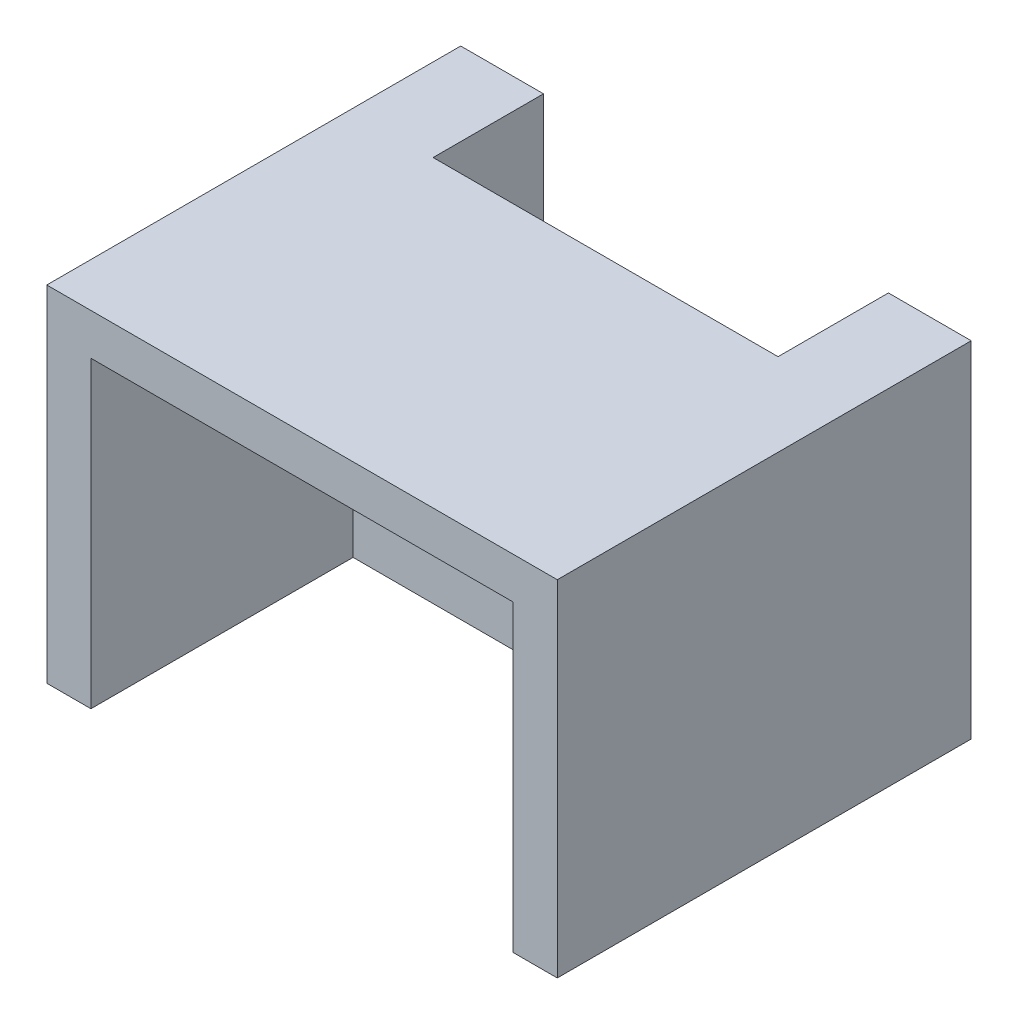
SolidWorks part; units mm, degrees
ref_plane "Front Plane" through (0, 0, 0) normal (0, 0, 1) x (1, 0, 0)
ref_plane "Top Plane" through (0, 0, 0) normal (0, 1, 0) x (1, 0, 0)
ref_plane "Right Plane" through (0, 0, 0) normal (1, 0, 0) x (0, 0, -1)
sketch "Sketch1" plane through (0, 0, 0) normal (1, 0, 0) x (0, 0, -1)
  line L0 (0, 0) -> (25, 0)
  line L1 (25, 0) -> (25, -25)
  line L2 (25, -25) -> (0, -25)
  line L3 (0, -25) -> (0, 0)
  dimension "D1" = 25
  dimension "D2" = 25
extrude "Boss-Extrude1" add sketch "Sketch1" along normal blind 37
sketch "Sketch2" plane through (0, -25, 0) normal (0, -1, 0) x (1, 0, 0)
  line L0 (3.2, 0) -> (3.2, -19)
  line L1 (37, 0) -> (0, 0) construction
  line L2 (3.2, -19) -> (33.8, -19)
  line L3 (33.8, -19) -> (33.8, 0)
  line L4 (33.8, 0) -> (3.2, 0)
  line L5 (18.5, -25) -> (18.5, -19) construction
  line L6 (37, -25) -> (0, -25) construction
  dimension "D1" = 30.6
  dimension "D2" = 6
extrude "Cut-Extrude1" cut sketch "Sketch2" against normal offset from surface (22 mm away) 3 up to face at (18.5, 0, -12.5)
sketch "Sketch3" plane through (0, 0, -25) normal (0, 0, -1) x (-1, 0, 0)
  line L0 (-37, 0) -> (0, 0) construction
  line L1 (-31, 0) -> (-6, 0)
  line L2 (-31, 0) -> (-31, -25)
  line L3 (-31, -25) -> (-6, -25)
  line L4 (-6, 0) -> (-6, -25)
  line L5 (-37, -25) -> (0, -25) construction
  line L6 (-18.5, 0) -> (-18.5, -25) construction
  dimension "D1" = 25
extrude "Cut-Extrude2" cut sketch "Sketch3" against normal blind 3
sketch "Sketch4" plane through (0, 0, -25) normal (0, 0, -1) x (-1, 0, 0)
  line L5 (-37, -25) -> (-31, -25)
  line L6 (-31, -25) -> (-31, 0)
  line L7 (-31, 0) -> (-37, 0)
  line L8 (-37, 0) -> (-37, -25)
  line L9 (-37, -25) -> (-31, -25)
  line L10 (-31, -25) -> (-31, 0)
  line L11 (-31, 0) -> (-37, 0)
  line L12 (-37, 0) -> (-37, -25)
  line L14 (0, 0) -> (-6, 0)
  line L15 (-6, 0) -> (-6, -25)
  line L16 (-6, -25) -> (0, -25)
  line L17 (0, -25) -> (0, 0)
  line L18 (0, 0) -> (-6, 0)
  line L19 (-6, 0) -> (-6, -25)
  line L20 (-6, -25) -> (0, -25)
  line L21 (0, -25) -> (0, 0)
  dimension "D1" = 0
  dimension "D2" = 0
extrude "Boss-Extrude2" add sketch "Sketch4" along normal blind 5
sketch "Sketch5" plane through (6, 0, 0) normal (1, 0, 0) x (0, 0, -1)
  line L0 (30, -15) -> (27.634, -15)
  line L1 (30, 0) -> (30, -25) construction
  line L2 (27.634, -15) -> (28.5, -23.5)
  line L3 (28.5, -23.5) -> (27.3943, -23.5)
  line L4 (27.3943, -23.5) -> (26.5283, -15)
  line L5 (26.5283, -15) -> (22, -15)
  line L6 (22, -25) -> (22, 0) construction
  line L7 (22, -15) -> (22, -25)
  line L8 (22, -25) -> (30, -25)
  line L9 (30, -25) -> (30, -15)
  line L10 (26.5283, -15) -> (25, 0) construction
  line L11 (22, 0) -> (30, 0) construction
  point P4 (27.6242, -23.4538)
  point P18 (0, 0)
  point P19 (24.3971, 0)
  dimension "D1" = 1.5
  dimension "D2" = 1.1
  dimension "D3" = 1.5
  dimension "D4" = 10
  dimension "D5" = 3
extrude "Boss-Extrude3" add sketch "Sketch5" along normal blind 0.8
sketch "Sketch6" plane through (31, 0, 0) normal (-1, 0, 0) x (0, 0, 1)
  line L8 (-30, -15) -> (-30, -25)
  line L9 (-27.634, -15) -> (-30, -15)
  line L10 (-28.5, -23.5) -> (-27.634, -15)
  line L11 (-27.3943, -23.5) -> (-28.5, -23.5)
  line L12 (-26.5283, -15) -> (-27.3943, -23.5)
  line L13 (-22, -15) -> (-26.5283, -15)
  line L14 (-22, -25) -> (-22, -15)
  line L15 (-30, -25) -> (-22, -25)
  line L16 (-30, -15) -> (-30, -25)
  line L17 (-27.634, -15) -> (-30, -15)
  line L18 (-28.5, -23.5) -> (-27.634, -15)
  line L19 (-27.3943, -23.5) -> (-28.5, -23.5)
  line L20 (-26.5283, -15) -> (-27.3943, -23.5)
  line L21 (-22, -15) -> (-26.5283, -15)
  line L22 (-22, -25) -> (-22, -15)
  line L23 (-30, -25) -> (-22, -25)
  dimension "D1" = 0
extrude "Boss-Extrude4" add sketch "Sketch6" along normal blind 0.8
